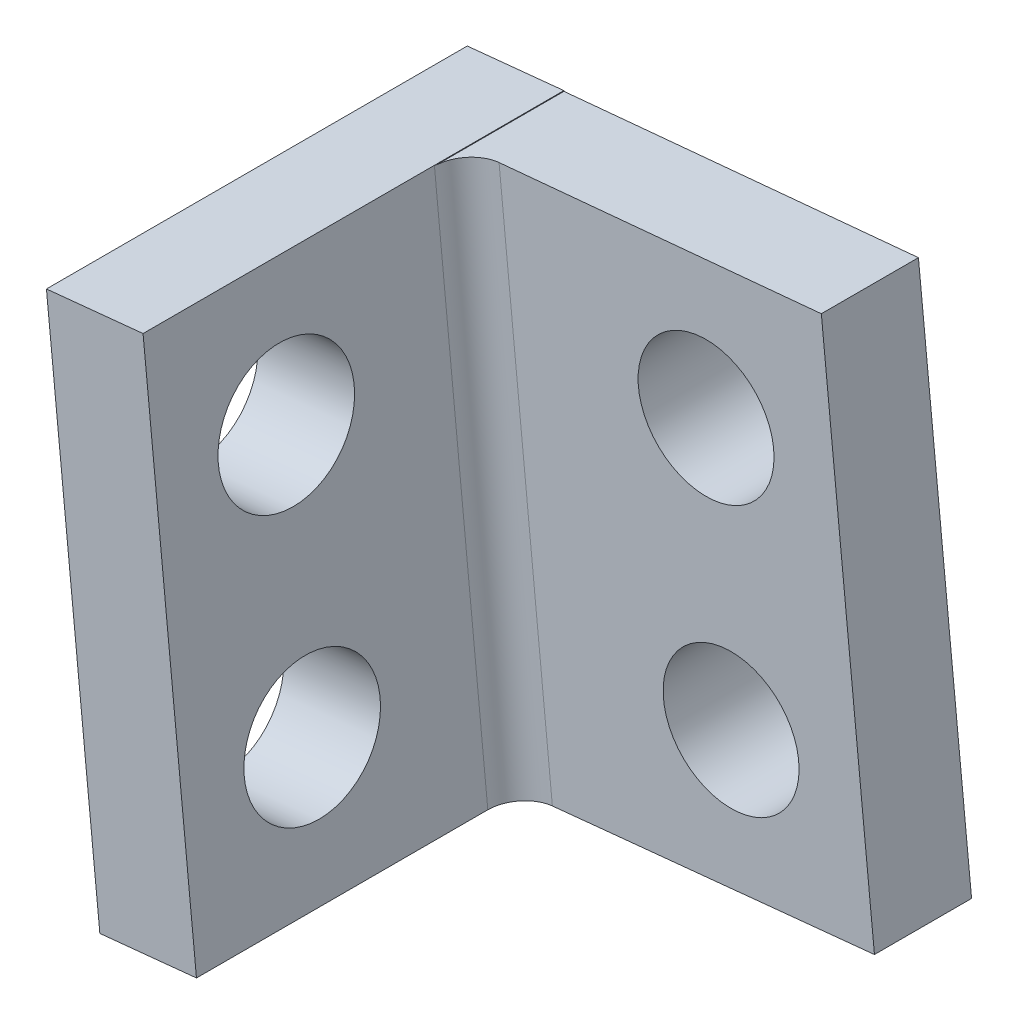
SolidWorks part; units mm, degrees
material "PLA"
ref_plane "Front Plane" through (0, 0, 0) normal (0, 0, 1) x (1, 0, 0)
ref_plane "Top Plane" through (0, 0, 0) normal (0, 1, 0) x (1, 0, 0)
ref_plane "Right Plane" through (0, 0, 0) normal (1, 0, 0) x (0, 0, -1)
sketch "Sketch1" plane through (0, 0, 0) normal (0, 0, 1) x (1, 0, 0)
  line L0 (-105, 44.7368) -> (-103.35, 28.3195)
  line L1 (-103.35, 28.3195) -> (-89.4202, 29.7195)
  line L2 (-89.4202, 29.7195) -> (-91.0612, 46.0439)
  line L3 (-91.0612, 46.0439) -> (-105, 44.7368)
  line L4 (-104.175, 36.5282) -> (-90.2407, 37.8817) construction
  line L5 (-94.622, 41.4749) -> (-93.8486, 33.5124) construction
  arc A0 (105, 44.7368) -> (-105, 44.7368) centre (0, -1000) ccw construction
  circle A2 centre (-94.622, 41.4749) radius 2.1
  circle A3 centre (-93.8486, 33.5124) radius 2.1
  point P17 (0, 0)
  point P18 (-94.622, 41.4749)
  point P19 (-93.8486, 33.5124)
  point P20 (0, 0)
  dimension "D2" = 4.2
  dimension "D1" = 14
  dimension "D3" = 4
  dimension "D4" = 4
extrude "Boss-Extrude1" add sketch "Sketch1" along normal blind 3
sketch "Sketch3" plane through (-99.4987, -10, 0) normal (-0.995, -0.1, 0) x (0, 0, 1)
  line L0 (0, 55.0126) -> (0, 38.5126) construction
  line L1 (0, 38.5126) -> (13, 38.5126)
  line L2 (0, 38.5126) -> (0, 55.0126)
  line L3 (0, 55.0126) -> (13, 55.0126)
  line L4 (13, 38.5126) -> (13, 55.0126)
  line L5 (3, 38.5126) -> (0, 38.5126) construction
  line L6 (3, 55.0126) -> (0, 55.0126) construction
  line L7 (3, 55.0126) -> (3, 38.5126) construction
  line L8 (3, 46.7626) -> (13, 46.7626) construction
  circle A0 centre (9, 42.7626) radius 2.1
  circle A1 centre (9, 50.7626) radius 2.1
  point P19 (0, 0)
  point P20 (0, 0)
  point P21 (0, 0)
  dimension "D2" = 4.2
  dimension "D1" = 10
  dimension "D3" = 4
  dimension "D4" = 6
extrude "Boss-Extrude2" add sketch "Sketch3" against normal blind 3
fillet "Fillet1" radius 1 1 edges at (-101.189, 36.8182, 3)
